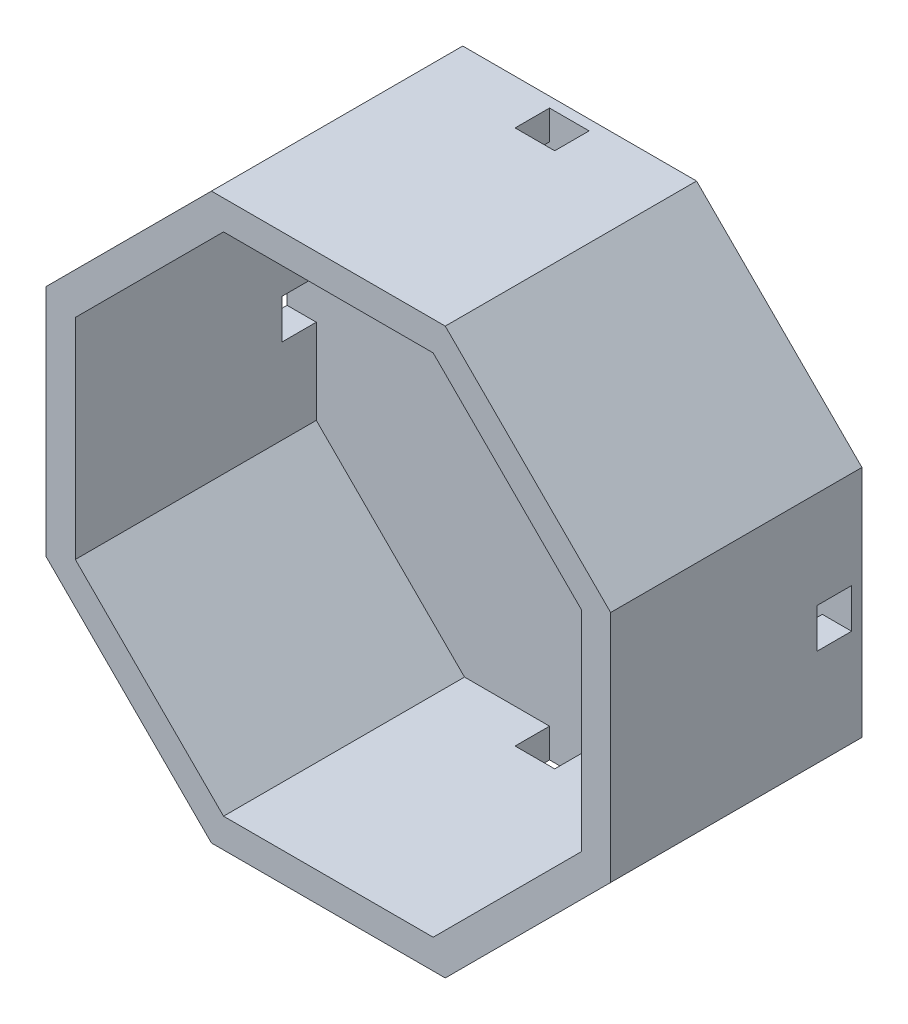
SolidWorks part; units mm, degrees
ref_plane "Front Plane" through (0, 0, 0) normal (0, 0, 1) x (1, 0, 0)
ref_plane "Top Plane" through (0, 0, 0) normal (0, 1, 0) x (1, 0, 0)
ref_plane "Right Plane" through (0, 0, 0) normal (1, 0, 0) x (0, 0, -1)
sketch "Sketch1" plane through (0, 0, 0) normal (0, 1, 0) x (1, 0, 0)
  line L0 (0, 0) -> (0, -82) construction
  line L1 (-33.965, -82) -> (33.965, -82)
  line L2 (-82, 0) -> (82, 0)
  line L3 (-33.965, 82) -> (33.965, 82)
  line L4 (-82, 33.965) -> (-82, -33.965)
  line L5 (82, 33.965) -> (82, -33.965)
  line L6 (-82, -33.965) -> (-33.965, -82)
  line L7 (-82, 33.965) -> (-33.965, 82)
  line L8 (33.965, 82) -> (82, 33.965)
  line L9 (33.965, -82) -> (82, -33.965)
  point P8 (0, 0)
  point P13 (-82, 0)
  dimension "D1" = 67.93
  dimension "D2" = 164
  dimension "D3" = 67.93
  dimension "D4" = 164
extrude "Boss-Extrude1" add sketch "Sketch1" along normal blind 3 contours L0 L2 L4 L6 L1 | L2 L0 L1 L9 L5 | L8 L3 L7 L4 L2 L5
sketch "Sketch2" plane through (0, 3, 0) normal (0, 1, 0) x (1, 0, 0)
  line L0 (0, 82) -> (0, 73.5)
  line L1 (-30.4442, 73.5) -> (30.4442, 73.5)
  line L2 (-82, 0) -> (82, 0) construction
  line L3 (0, 82) -> (0, -82) construction
  line L4 (-30.4442, -73.5) -> (30.4442, -73.5)
  line L5 (-73.5, -30.4442) -> (-73.5, 30.4442)
  line L6 (73.5, -30.4442) -> (73.5, 30.4442)
  line L7 (-73.5, 30.4442) -> (-30.4442, 73.5)
  line L8 (33.965, -82) -> (82, -33.965)
  line L9 (82, -33.965) -> (82, 33.965)
  line L10 (82, 33.965) -> (33.965, 82)
  line L11 (33.965, 82) -> (-33.965, 82)
  line L12 (-33.965, 82) -> (-82, 33.965)
  line L13 (-82, 33.965) -> (-82, -33.965)
  line L14 (-82, -33.965) -> (-33.965, -82)
  line L15 (-33.965, -82) -> (33.965, -82)
  line L16 (33.965, -82) -> (82, -33.965)
  line L17 (82, -33.965) -> (82, 33.965)
  line L18 (82, 33.965) -> (33.965, 82)
  line L19 (33.965, 82) -> (-33.965, 82)
  line L20 (-33.965, 82) -> (-82, 33.965)
  line L21 (-82, 33.965) -> (-82, -33.965)
  line L22 (-82, -33.965) -> (-33.965, -82)
  line L23 (-33.965, -82) -> (33.965, -82)
  line L24 (30.4442, 73.5) -> (73.5, 30.4442)
  line L25 (73.5, -30.4442) -> (30.4442, -73.5)
  line L26 (-30.4442, -73.5) -> (-73.5, -30.4442)
  point P10 (0, 73.5)
  point P22 (-73.5, 0)
  dimension "D2" = 8.5
  dimension "D3" = 8.5
  dimension "D4" = 8.5
  dimension "D1" = 0
extrude "Boss-Extrude2" add sketch "Sketch2" along normal blind 70
sketch "Sketch3" plane through (82, 0, 0) normal (1, 0, 0) x (0, 0, -1)
  line L0 (0, 0) -> (0, 3)
  line L1 (-33.965, 3) -> (33.965, 3)
  line L2 (33.965, 73) -> (33.965, 0) construction
  line L4 (-5.75, 3) -> (5.75, 3)
  line L5 (5.75, 3) -> (5.75, 13)
  line L6 (5.75, 13) -> (-5.75, 13)
  line L7 (-5.75, 13) -> (-5.75, 3)
  point P8 (0, 3)
  point P12 (0, 0)
  point P15 (0, 3)
  dimension "D1" = 3
  dimension "D2" = 11.5
  dimension "D3" = 10
extrude "Cut-Extrude1" cut sketch "Sketch3" against normal blind 170 contours L6 L7 L1 L5
sketch "Sketch4" plane through (0, 0, -82) normal (0, 0, -1) x (-1, 0, 0)
  line L0 (0, 0) -> (0, 3)
  line L1 (-5.75, 3) -> (5.75, 3)
  line L2 (-5.75, 3) -> (-5.75, 13)
  line L3 (-5.75, 13) -> (5.75, 13)
  line L4 (5.75, 13) -> (5.75, 3)
  point P6 (0, 3)
  dimension "D1" = 3
  dimension "D2" = 11.5
  dimension "D3" = 10
extrude "Cut-Extrude2" cut sketch "Sketch4" against normal blind 170 contours L4 L3 L2 L1
move or copy body "Body-Move/Copy2" bodies to move or copy 104 copy no rotation origin (0, 36.5, 0) rotation axis (1, 0, 0) rotation angle 90
